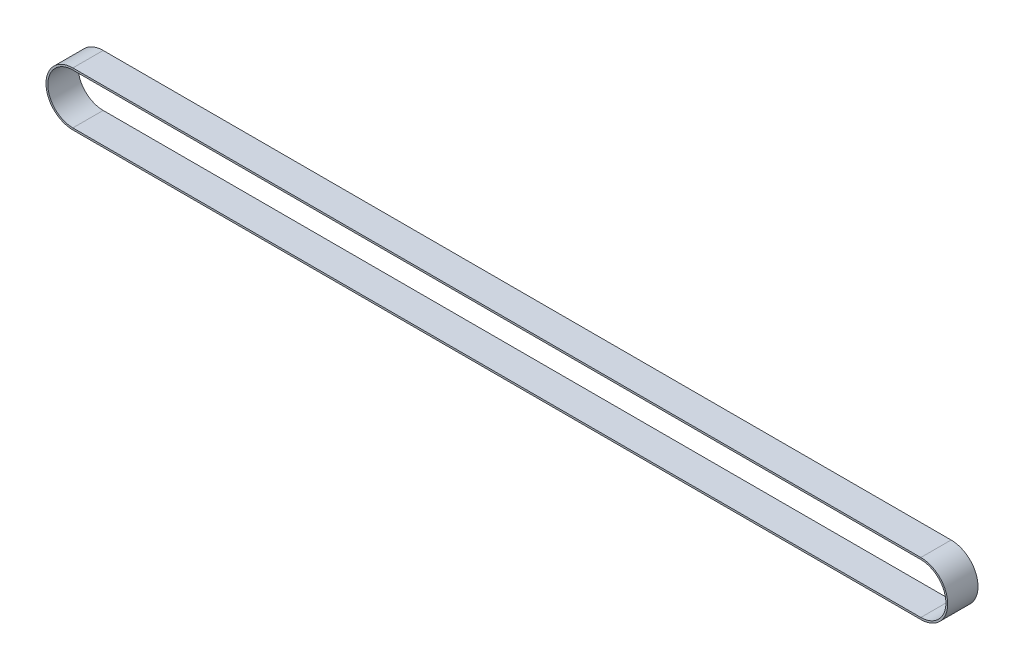
SolidWorks part; units mm, degrees
ref_plane "前视基准面" through (0, 0, 0) normal (0, 0, 1) x (1, 0, 0)
ref_plane "上视基准面" through (0, 0, 0) normal (0, 1, 0) x (1, 0, 0)
ref_plane "右视基准面" through (0, 0, 0) normal (1, 0, 0) x (0, 0, -1)
other "Configuration Table"
sketch "草图1" plane through (0, 0, 0) normal (0, 0, 1) x (1, 0, 0)
  line L0 (0, 0) -> (700, 0) construction
  line L1 (0, 20.69) -> (700, 20.69)
  line L2 (0, -20.69) -> (700, -20.69)
  arc A0 (0, 20.69) -> (0, -20.69) centre (0, 0) ccw
  arc A1 (700, -20.69) -> (700, 20.69) centre (700, 0) ccw
  point P3 (350, 0)
  dimension "D2" = 20.69
  dimension "D1" = 700
extrude "拉伸-薄壁1" add sketch "草图1" along normal blind 25 thin thin type one direction wall 1.5
